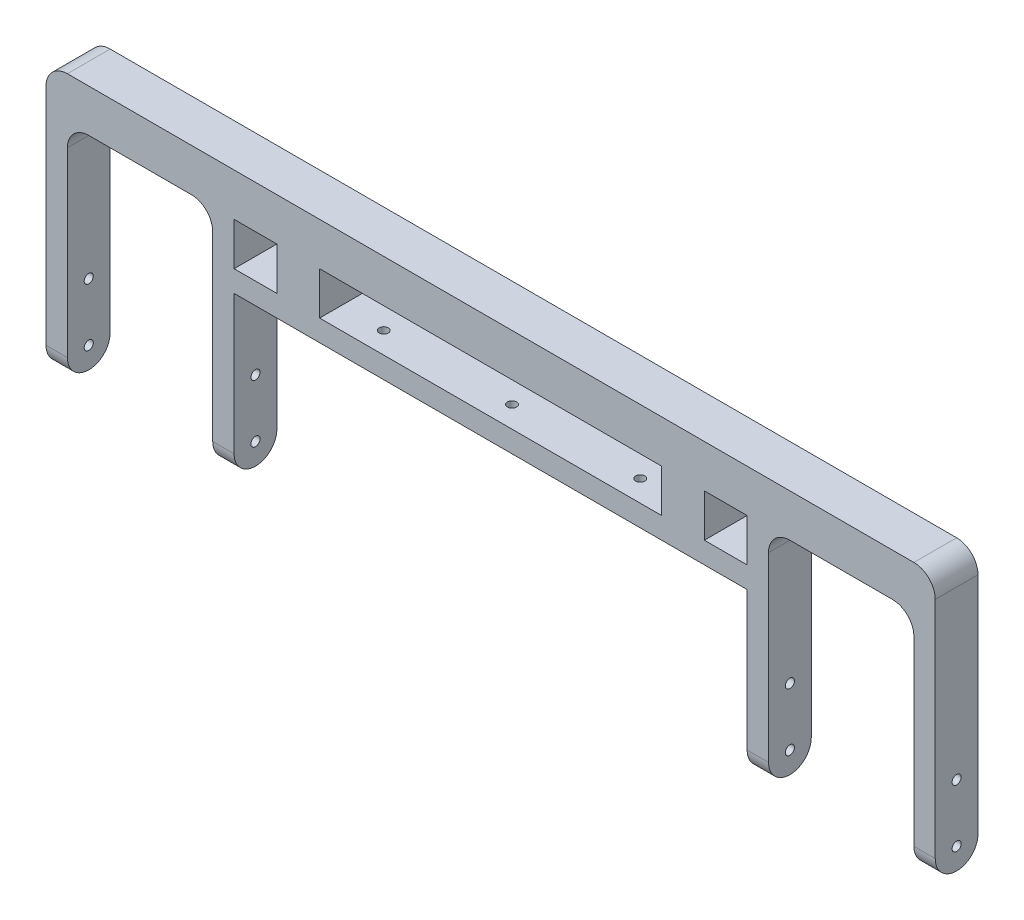
SolidWorks part; units mm, degrees
ref_plane "Front Plane" through (0, 0, 0) normal (0, 0, 1) x (1, 0, 0)
ref_plane "Top Plane" through (0, 0, 0) normal (0, 1, 0) x (1, 0, 0)
ref_plane "Right Plane" through (0, 0, 0) normal (1, 0, 0) x (0, 0, -1)
sketch "Sketch2" plane through (0, 0, 0) normal (0, 0, 1) x (1, 0, 0)
  line L1 (0, 0) -> (240, 0)
  line L2 (0, 0) -> (0, 10)
  line L3 (0, 10) -> (240, 10)
  line L4 (240, 0) -> (240, 10)
  dimension "D1" = 240
  dimension "D2" = 10
extrude "Boss-Extrude1" add sketch "Sketch2" along normal blind 20
sketch "Sketch3" plane through (0, 10, 0) normal (0, 1, 0) x (1, 0, 0)
  line L0 (240, -20) -> (0, -20) construction
  line L1 (0, -20) -> (0, 0) construction
  circle A0 centre (60, -10) radius 2.125
  circle A1 centre (120, -10) radius 2.125
  circle A2 centre (180, -10) radius 2.125
  dimension "D2" = 4.25
  dimension "D3" = 4.25
  dimension "D4" = 4.25
  dimension "D1" = 10
  dimension "D5" = 60
  dimension "D6" = 60
  dimension "D7" = 60
extrude "Cut-Extrude1" cut sketch "Sketch3" against normal blind 20
sketch "Sketch4" plane through (0, 10, 0) normal (0, 1, 0) x (1, 0, 0)
  line L0 (240, 0) -> (0, 0) construction
  line L1 (20, 0) -> (40, 0)
  line L2 (20, 0) -> (20, -20)
  line L3 (20, -20) -> (40, -20)
  line L4 (40, 0) -> (40, -20)
  line L5 (240, -20) -> (0, -20) construction
  line L6 (0, -20) -> (0, 0) construction
  line L7 (200, 0) -> (220, 0)
  line L8 (200, 0) -> (200, -20)
  line L9 (200, -20) -> (220, -20)
  line L10 (220, 0) -> (220, -20)
  line L11 (240, -20) -> (240, 0) construction
  dimension "D1" = 20
  dimension "D2" = 20
  dimension "D3" = 20
  dimension "D4" = 20
extrude "Boss-Extrude2" add sketch "Sketch4" along normal blind 20
sketch "Sketch5" plane through (0, 30, 0) normal (0, 1, 0) x (1, 0, 0)
  line L0 (40, 0) -> (20, 0) construction
  line L1 (-88, 0) -> (328, 0)
  line L2 (-88, 0) -> (-88, -20)
  line L3 (-88, -20) -> (328, -20)
  line L4 (328, 0) -> (328, -20)
  line L5 (0, -20) -> (0, 0) construction
  line L6 (240, -20) -> (240, 0) construction
  dimension "D1" = 20
  dimension "D2" = 0
  dimension "D3" = 88
  dimension "D4" = 88
extrude "Boss-Extrude3" add sketch "Sketch5" along normal blind 20
sketch "Sketch6" plane through (0, 30, 0) normal (0, -1, 0) x (1, 0, 0)
  line L0 (328, 0) -> (220, 0) construction
  line L1 (240, 20) -> (250, 20)
  line L2 (240, 20) -> (240, 0)
  line L3 (240, 0) -> (250, 0)
  line L4 (250, 20) -> (250, 0)
  line L5 (20, 0) -> (-88, 0) construction
  line L6 (0, 20) -> (-10, 20)
  line L7 (0, 20) -> (0, 0)
  line L8 (0, 0) -> (-10, 0)
  line L9 (-10, 20) -> (-10, 0)
  line L11 (328, 20) -> (318, 20)
  line L12 (328, 20) -> (328, 0)
  line L13 (328, 0) -> (318, 0)
  line L14 (318, 20) -> (318, 0)
  line L15 (-88, 20) -> (-78, 20)
  line L16 (-88, 20) -> (-88, 0)
  line L17 (-88, 0) -> (-78, 0)
  line L18 (-78, 20) -> (-78, 0)
  dimension "D1" = 10
  dimension "D2" = 10
  dimension "D3" = 10
  dimension "D4" = 10
extrude "Boss-Extrude4" add sketch "Sketch6" along normal blind 95
sketch "Sketch7" plane through (-88, 0, 0) normal (-1, 0, 0) x (0, 0, 1)
  line L0 (20, -65) -> (0, -65) construction
  line L1 (0, 50) -> (0, -65) construction
  line L2 (0, -65) -> (20, -65)
  arc A0 (0, -65) -> (20, -65) centre (10, -65) ccw
extrude "Boss-Extrude5" add sketch "Sketch7" against normal up to surface (416 mm away) up to face at (328, -7.5, 10)
sketch "Sketch8" plane through (0, 0, 0) normal (0, 0, -1) x (-1, 0, 0)
  line L0 (-328, -75) -> (88, -75) construction
  line L1 (-318, -65) -> (-250, -65)
  line L2 (-318, -65) -> (-318, -75)
  line L3 (-318, -75) -> (-250, -75)
  line L4 (-250, -65) -> (-250, -75)
  line L6 (-250, -75) -> (-250, -44.0273)
  line L9 (-240, -65) -> (0, -65)
  line L10 (-240, -65) -> (-240, -75)
  line L11 (-240, -75) -> (0, -75)
  line L12 (0, -65) -> (0, -75)
  line L13 (-250, -65) -> (-250, 30) construction
  line L14 (10, -65) -> (78, -65)
  line L15 (10, -65) -> (10, -75)
  line L16 (10, -75) -> (78, -75)
  line L17 (78, -65) -> (78, -75)
  line L19 (78, -65) -> (78, 30) construction
  dimension "D1" = 10
  dimension "D2" = 0
  dimension "D3" = 240
  dimension "D4" = 10
  dimension "D5" = 0
extrude "Cut-Extrude2" cut sketch "Sketch8" against normal blind 65 contours L10 L9 L12 L11 | L2 L1 L4 L3 | L15 L14 L17 L16
sketch "Sketch9" plane through (-88, 0, 0) normal (-1, 0, 0) x (0, 0, 1)
  line L0 (0, 50) -> (20, 50) construction
  line L1 (20, 50) -> (20, -65) construction
  circle A0 centre (10, -38) radius 2.125
  dimension "D2" = 4.25
  dimension "D1" = 88
  dimension "D3" = 10
extrude "Cut-Extrude3" cut sketch "Sketch9" against normal up to surface (416 mm away) up to face at (328, -10, 10)
fillet "Fillet1" radius 10 6 edges at (318, 30, 10) (250, 30, 10) (-78, 30, 10) (-10, 30, 10) (-88, 50, 10) (328, 50, 10)
sketch "Sketch10" plane through (328, 0, 0) normal (1, 0, 0) x (0, 0, -1)
  line L0 (-20, 50) -> (0, 50) construction
  line L1 (0, 40) -> (0, -65) construction
  circle A0 centre (-10, -65) radius 2.125
  dimension "D1" = 4.25
  dimension "D2" = 115
  dimension "D3" = 10
extrude "Cut-Extrude4" cut sketch "Sketch10" against normal up to surface (416 mm away) up to face at (-88, -38, 12.125)
